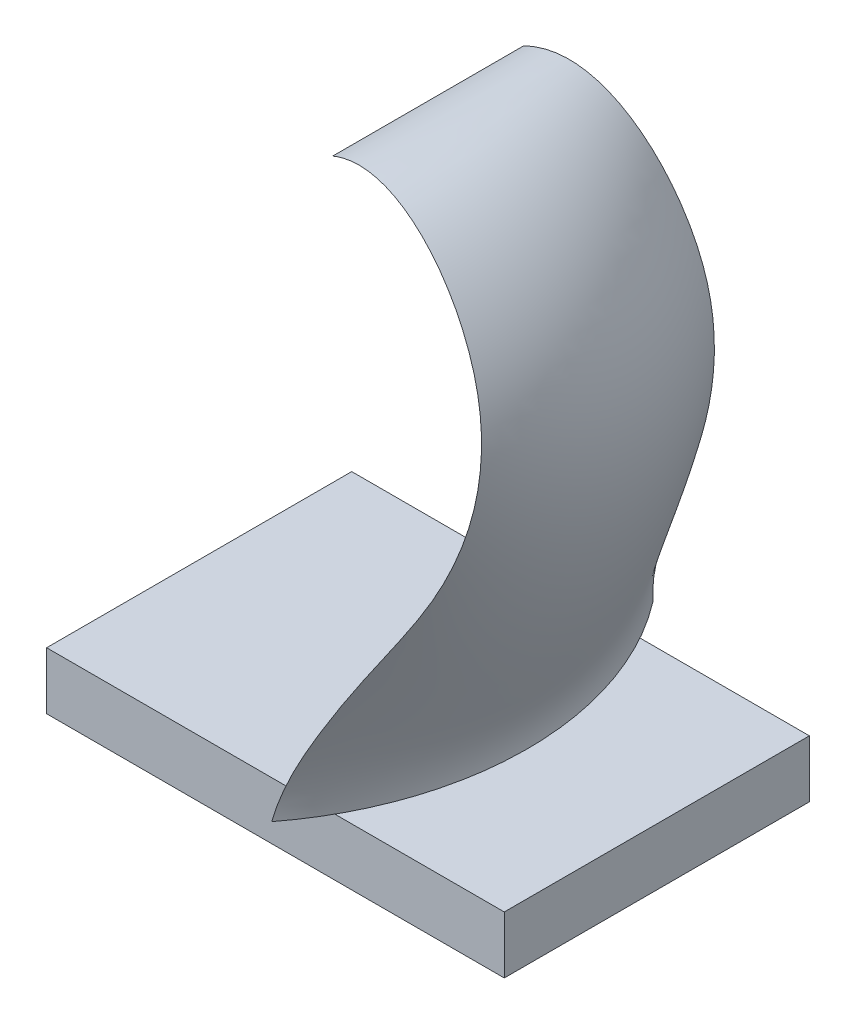
SolidWorks part; units mm, degrees
ref_plane "Front Plane" through (0, 0, 0) normal (0, 0, 1) x (1, 0, 0)
ref_plane "Top Plane" through (0, 0, 0) normal (0, 1, 0) x (1, 0, 0)
ref_plane "Right Plane" through (0, 0, 0) normal (1, 0, 0) x (0, 0, -1)
sketch "FrontSketch" plane through (0, 0, 0) normal (0, 0, 1) x (1, 0, 0)
  line L0 (152.4, 0) -> (-152.4, 0) construction
  line L1 (0, 0) -> (0, 482.6) construction
  line L2 (415.7271, 0) -> (-415.7271, 0) construction
  line L3 (-152.4, 0) -> (-152.4, 38.1) construction
  line L4 (-152.4, 38.1) -> (152.4, 38.1) construction
  line L5 (152.4, 38.1) -> (152.4, 0) construction
  line L6 (-283.3983, 169.5855) -> (472.4692, 169.5855) construction
  line L7 (230.8924, 79.7004) -> (-36.9365, 79.7004) construction
  line L8 (344.3268, 292.3794) -> (-241.2533, 292.3794) construction
  line L9 (-112.4138, 378.8263) -> (305.579, 378.8263) construction
  line L10 (-117.2676, 482.6) -> (117.2676, 482.6) construction
  line L11 (-21.9385, 378.8263) -> (21.9385, 378.8263) construction
  line L12 (0, 482.6) -> (-88.9749, 482.6) construction
  line L13 (66.04, 48.2683) -> (66.04, 27.9317) construction
  spline S0 degree 3 poles (152.4, 38.1) (151.3344, 71.5579) (166.3427, 141.563) (228.1216, 220.754) (242.1984, 388.2763) (150.452, 482.6) (0, 482.6) knots 0 0 0 0 0.173487 0.360866 0.507833 1 1 1 1
  spline S1 degree 3 poles (22.86, 38.1) (34.1935, 92.778) (93.9741, 161.2849) (124.9198, 282.0807) (76.7739, 367.1761) (27.4231, 378.8263) (0, 378.8263) knots 0 0 0 0 0.38113 0.643813 0.826905 1 1 1 1
  spline S2 degree 3 poles (66.04, 38.1) (66.04, 51.7893) (86.6585, 96.0148) (124.0398, 177.444) (150.5652, 314.7964) (52.3199, 402.7479) (0, 378.8263) knots 0 0 0 0 0.094543 0.326232 0.638152 1 1 1 1
  point P4 (0, 0)
  point P26 (190.4377, 169.5855)
  point P28 (116.4485, 169.5855)
  point P29 (85.9646, 169.5855)
  point P32 (155.2514, 79.7004)
  point P33 (79.0222, 79.7004)
  point P34 (36.5574, 79.7004)
  point P36 (232.0403, 292.3794)
  point P38 (127.5155, 292.3794)
  point P39 (110.0632, 292.3794)
  point P42 (213.3768, 378.8263)
  point P43 (58.234, 378.8263)
  point P44 (0, 378.8263)
  point P47 (125.8621, 298.118)
  point P48 (111.6159, 283.6932)
  point P49 (32.6271, 375.5925)
  point P54 (127.5155, 292.3794)
  point P56 (107.0393, 466.987)
  point P57 (135.127, 455.4199)
  dimension "D1" = 38.1
  dimension "D2" = 304.8
  dimension "D3" = 482.6
  dimension "D4" = 43.18
  dimension "D5" = 86.36
sketch "TopSketch" plane through (0, 0, 0) normal (0, 1, 0) x (1, 0, 0)
  line L1 (-152.4, 101.6) -> (-152.4, -101.6) construction
  line L2 (-152.4, 101.6) -> (152.4, 101.6)
  line L3 (-152.4, 101.6) -> (-152.4, -101.6)
  line L4 (-152.4, -101.6) -> (152.4, -101.6)
  line L5 (152.4, 101.6) -> (152.4, -101.6)
  point P3 (-152.4, 0)
  point P17 (-152.4, 0)
  dimension "D3" = 203.2
extrude "Boss-Extrude1" add sketch "TopSketch" along normal blind 38.1 contours L3 L2 L5 L4
sketch "Sketch4" plane through (0, 38.1, 0) normal (0, 1, 0) x (1, 0, 0)
  line L0 (22.86, 101.6) -> (22.86, -101.6) construction
  line L3 (66.04, 101.6) -> (66.04, -101.6) construction
  line L4 (28.6176, 139.7) -> (28.6176, -139.7) construction
  ellipse E0 centre (22.86, 0) end of major axis (152.4, 0) minor radius 101.6 (22.86, -101.6) -> (22.86, 101.6) ccw
  point P9 (66.04, 0)
  dimension "D1" = 279.4
  dimension "D2" = 203.2
  dimension "D3" = 203.2
sketch3d "3DSketch7"
  spline S0 degree 3 poles (152.4, 38.1, 0) (151.3344, 71.5579, 0) (166.3427, 141.563, 0) (228.1216, 220.754, 0) (242.1984, 388.2763, 0) (150.452, 482.6, 0) (0, 482.6, 0) knots 0 0 0 0 0.173487 0.360866 0.507833 1 1 1 1 construction
sketch3d "3DSketch8"
  spline S0 degree 3 poles (152.4, 38.1, 0) (151.3344, 71.5579, 0) (166.3427, 141.563, 0) (228.1216, 220.754, 0) (242.1984, 388.2763, 0) (150.452, 482.6, 0) (0, 482.6, 0) knots 0 0 0 0 0.173487 0.360866 0.507833 1 1 1 1 construction
sketch3d "3DSketch9"
  spline S0 degree 3 poles (152.4, 38.1, 0) (151.3344, 71.5579, 0) (166.3427, 141.563, 0) (228.1216, 220.754, 0) (242.1984, 388.2763, 0) (150.452, 482.6, 0) (0, 482.6, 0) knots 0 0 0 0 0.173487 0.360866 0.507833 1 1 1 1 construction
sketch3d "3DSketch12"
sketch "Sketch11" plane through (0, 0, 0) normal (-1, 0, 0) x (0, 0, 1)
  line L0 (-50.8, 378.8263) -> (50.8, 378.8263) construction
  ellipse E0 centre (0, 378.8263) end of major axis (0, 275.0525) minor radius 50.8 (50.8, 378.8263) -> (-50.8, 378.8263) ccw
  dimension "D1" = 101.6
sketch "Sketch8" plane through (17.2607, 102.8569, 0) normal (0.1655, 0.9862, 0) x (0.9862, -0.1655, 0)
  line L0 (28.6464, 88.9) -> (28.6464, -88.9) construction
  ellipse E0 centre (28.6464, 0) end of major axis (-82.6274, 0) minor radius 88.9 (28.6464, -88.9) -> (28.6464, 88.9) ccw
  dimension "D1" = 177.8
sketch "Sketch9" plane through (121.3296, 209.5912, 0) normal (0.501, 0.8654, 0) x (0.8654, -0.501, 0)
  line L0 (-17.811, 76.2) -> (-17.811, -76.2) construction
  ellipse E0 centre (-17.811, 0) end of major axis (-115.4742, 0) minor radius 76.2 (-17.811, -76.2) -> (-17.811, 76.2) ccw
  dimension "D1" = 152.4
sketch "Sketch10" plane through (-108.5084, 220.2367, 0) normal (-0.442, 0.897, 0) x (0.897, 0.442, 0)
  line L0 (231.6775, 63.5) -> (231.6775, -63.5) construction
  ellipse E0 centre (231.6775, 0) end of major axis (358.8324, 0) minor radius 63.5 (231.6775, -63.5) -> (231.6775, 63.5) ccw
  dimension "D1" = 127
sketch "Sketch12" plane through (2.652, 294.4454, 0) normal (0.009, 1, 0) x (1, -0.009, 0)
  line L0 (107.1724, 69.85) -> (107.1724, -69.85) construction
  ellipse E0 centre (107.1724, 0) end of major axis (229.3977, 0) minor radius 69.85 (107.1724, -69.85) -> (107.1724, 69.85) ccw
  dimension "D1" = 139.7
surface "Surface-Loft5"
sketch "Sketch15" plane through (0, 38.1, 0) normal (0, 1, 0) x (1, 0, 0)
  line L0 (22.86, 127) -> (22.86, -127) construction
  arc A0 (22.86, 127) -> (22.86, -127) centre (-142.3147, 0) cw
  point P3 (66.04, 0)
  point P7 (22.86, 0)
  dimension "D1" = 254
sketch3d "3DSketch14"
  spline S0 degree 3 poles (66.04, 38.1, 0) (66.04, 51.7893, 0) (86.6585, 96.0148, 0) (124.0398, 177.444, 0) (150.5652, 314.7964, 0) (52.3199, 402.7479, 0) (0, 378.8263, 0) knots 0 0 0 0 0.094543 0.326232 0.638152 1 1 1 1 construction
sketch3d "3DSketch15"
  spline S0 degree 3 poles (66.04, 38.1, 0) (66.04, 51.7893, 0) (86.6585, 96.0148, 0) (124.0398, 177.444, 0) (150.5652, 314.7964, 0) (52.3199, 402.7479, 0) (0, 378.8263, 0) knots 0 0 0 0 0.094543 0.326232 0.638152 1 1 1 1 construction
sketch3d "3DSketch19"
  point P3 (125.8621, 298.118, 0)
sketch3d "3DSketch22"
  spline S0 degree 3 poles (22.86, 38.1, 0) (34.1935, 92.778, 0) (93.9741, 161.2849, 0) (124.9198, 282.0807, 0) (76.7739, 367.1761, 0) (27.4231, 378.8263, 0) (0, 378.8263, 0) knots 0 0 0 0 0.38113 0.643813 0.826905 1 1 1 1 construction
sketch3d "3DSketch25"
  line L0 (-112.4138, 378.8263, 0) -> (305.579, 378.8263, 0) construction
sketch "Sketch16" plane through (0, 378.8263, 0) normal (0, 1, 0) x (1, 0, 0)
  line L0 (0, 63.5) -> (0, -63.5)
  point P4 (0, 0)
  dimension "D1" = 127
sketch "Sketch17" plane through (44.4169, 95.7527, 0) normal (0.4208, 0.9072, 0) x (0.9072, -0.4208, 0)
  line L0 (-0.1188, 114.3) -> (-0.1188, -114.3) construction
  arc A0 (-0.1188, 114.3) -> (-0.1188, -114.3) centre (-151.6926, 0) cw
  point P3 (-175.6802, 35.541)
  point P4 (38.1471, 0)
  point P5 (-0.1188, 0)
  dimension "D1" = 228.6
sketch "Sketch18" plane through (62.7088, 187.5534, 0) normal (0.3171, 0.9484, 0) x (0.9484, -0.3171, 0)
  line L0 (29.1246, 88.9) -> (29.1246, -88.9) construction
  arc A0 (29.1246, 88.9) -> (29.1246, -88.9) centre (-100.5951, 0) cw
  point P3 (56.6639, 0)
  point P4 (29.1246, 0)
  dimension "D1" = 177.8
sketch "Sketch20" plane through (-37.3514, 262.4962, 0) normal (-0.1409, 0.99, 0) x (0.99, 0.1409, 0)
  line L0 (150.4678, 76.2) -> (150.4678, -76.2) construction
  arc A0 (150.4678, 76.2) -> (150.4678, -76.2) centre (-6.0213, 0) cw
  point P3 (35.3052, 0)
  point P4 (168.0341, 0)
  point P10 (150.4678, 0)
  dimension "D1" = 152.4
surface "Surface-Loft7"
sketch3d "3DSketch27"
  spline S0 degree 3 poles (152.4, 38.1, 0) (151.3344, 71.5579, 0) (166.3427, 141.563, 0) (228.1216, 220.754, 0) (242.1984, 388.2763, 0) (150.452, 482.6, 0) (0, 482.6, 0) knots 0 0 0 0 0.173487 0.360866 0.507833 1 1 1 1 construction
sketch "Sketch21" plane through (-72.8647, 36.1465, 0) normal (-0.8958, 0.4444, 0) x (0, 0, 1)
  line L0 (-69.85, 348.1711) -> (69.85, 348.1711) construction
  ellipse E0 centre (0, 348.1711) end of major axis (0, 228.3136) minor radius 69.85 (69.85, 348.1711) -> (-69.85, 348.1711) ccw
  point P3 (0, 0)
  point P11 (0, 0)
  dimension "D1" = 139.7
